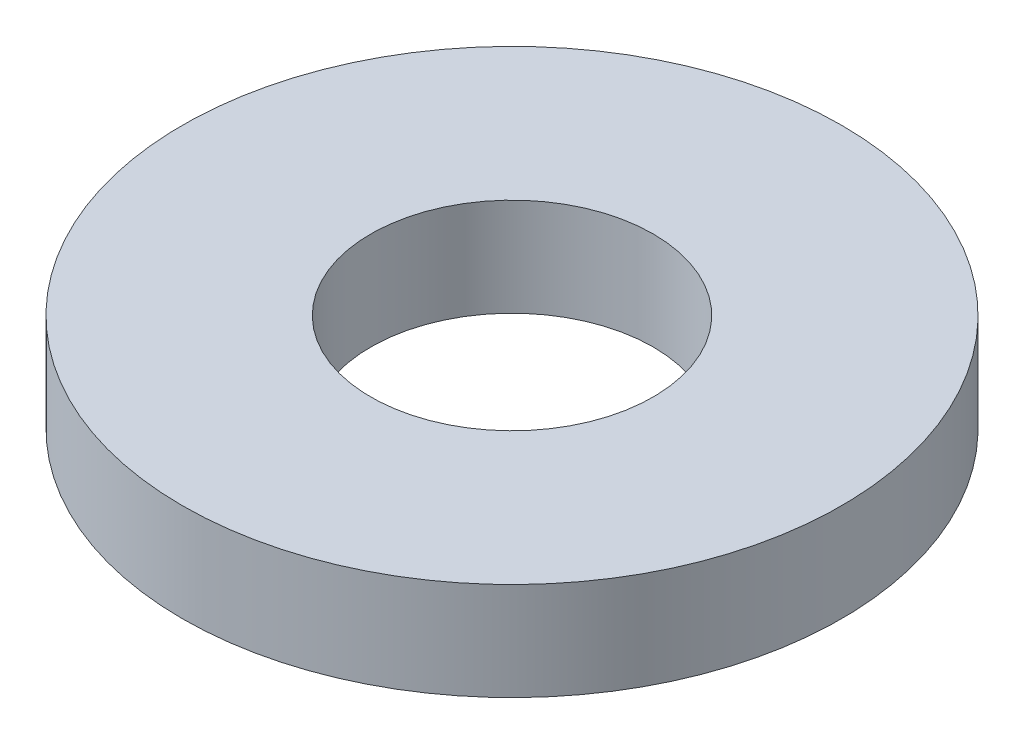
SolidWorks part; units mm, degrees
ref_plane "Front Plane" through (0, 0, 0) normal (0, 0, 1) x (1, 0, 0)
ref_plane "Top Plane" through (0, 0, 0) normal (0, 1, 0) x (1, 0, 0)
ref_plane "Right Plane" through (0, 0, 0) normal (1, 0, 0) x (0, 0, -1)
sketch "Sketch1" plane through (0, 0, 0) normal (1, 0, 0) x (0, 0, -1)
  line L0 (0, 0.8255) -> (0, -0.8255) construction
  line L1 (-5.5562, -0.8255) -> (5.5562, -0.8255) construction
  line L2 (-2.3813, 0.8255) -> (2.3813, 0.8255) construction
  point P4 (0, 0)
  point P7 (0, -0.8255)
  point P11 (0, 0.8255)
  dimension "Thickness" = 1.651
  dimension "ID" = 4.7625
  dimension "OD" = 11.1125
sketch "Sketch2" plane through (0, 0, 0) normal (0, 1, 0) x (1, 0, 0)
  circle A0 centre (0, 0) radius 5.5562
  circle A1 centre (0, 0) radius 2.3813
extrude "Boss-Extrude1" add sketch "Sketch2" along normal up to vertex (0.8255 mm away) and the other way up to vertex (0.8255 mm away) up to point (0, 0.8255, 0) other way up to point (0, -0.8255, 0)
